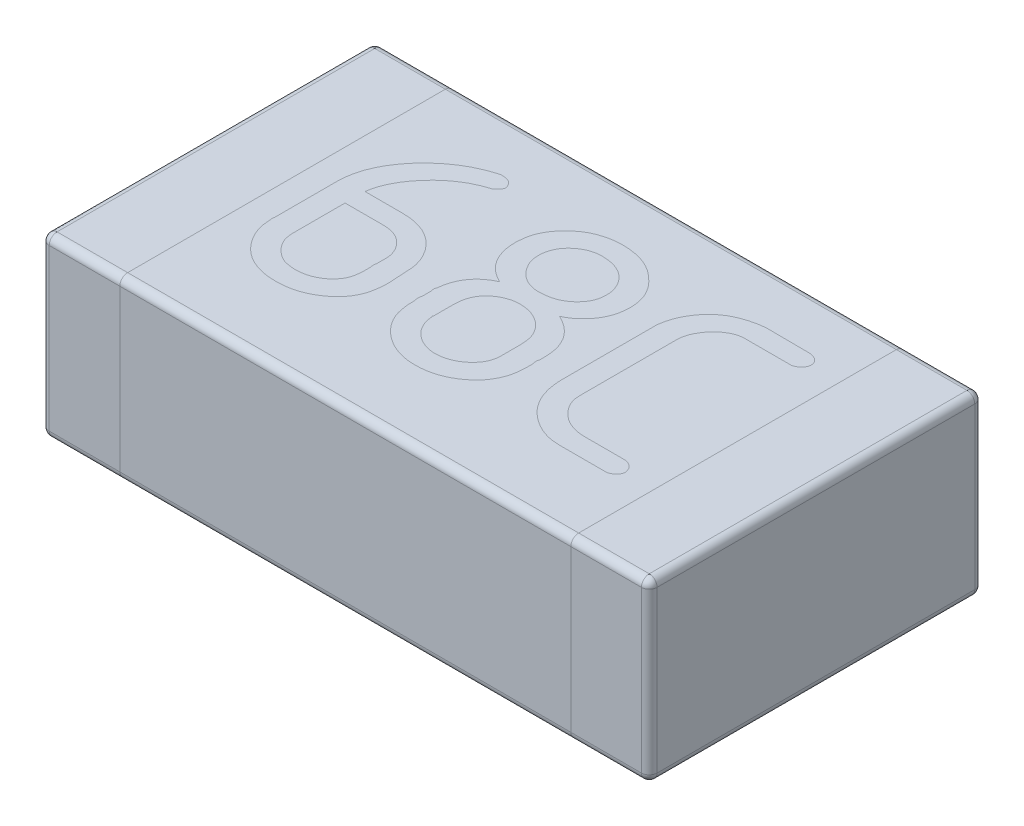
SolidWorks part; units mm, degrees
ref_plane "Front Plane" through (0, 0, 0) normal (0, 0, 1) x (1, 0, 0)
ref_plane "Top Plane" through (0, 0, 0) normal (0, 1, 0) x (1, 0, 0)
ref_plane "Right Plane" through (0, 0, 0) normal (1, 0, 0) x (0, 0, -1)
sketch "Sketch1" plane through (0, 0, 0) normal (0, 1, 0) x (1, 0, 0)
  line L1 (-0.755, -0.425) -> (0.755, -0.425)
  line L2 (-0.775, -0.405) -> (-0.775, 0.405)
  line L3 (-0.755, 0.425) -> (0.755, 0.425)
  line L4 (0.775, -0.405) -> (0.775, 0.405)
  line L5 (-0.775, -0.425) -> (0.775, 0.425) construction
  line L6 (-0.775, 0.425) -> (0.775, -0.425) construction
  arc A4 (-0.775, -0.405) -> (-0.755, -0.425) centre (-0.755, -0.405) ccw
  arc A5 (0.755, -0.425) -> (0.775, -0.405) centre (0.755, -0.405) ccw
  arc A6 (0.775, 0.405) -> (0.755, 0.425) centre (0.755, 0.405) ccw
  arc A7 (-0.755, 0.425) -> (-0.775, 0.405) centre (-0.755, 0.405) ccw
  point P0 (0, 0)
  dimension "D4" = 0.02
  dimension "D1" = 1.55
  dimension "D2" = 0.85
extrude "Boss-Extrude1" add sketch "Sketch1" along normal mid plane 0.45
sketch "Sketch3" plane through (0, 0.225, 0) normal (0, 1, 0) x (1, 0, 0)
  line L0 (-0.575, 0) -> (0.575, 0) construction
  line L1 (-0.575, -0.5133) -> (-0.575, 0.5133)
  line L2 (0.575, -0.5133) -> (0.575, 0.5133)
  line L3 (0, -0.25) -> (0, 0.25) construction
  line L6 (-0.575, -0.25) -> (0.575, -0.25) construction
  text T0 "<b>68C</b>" font "SWIsop1" height 0.53
  point P4 (0, 0)
  point P8 (-0.575, 0)
  point P11 (0.575, 0)
  point P14 (0, 0)
  point P17 (0, -0.25)
  dimension "D1" = 1.15
  dimension "D2" = 0.5
sketch "Sketch4" plane through (0, 0, 0.425) normal (0, 0, 1) x (1, 0, 0)
  line L0 (-0.575, 0.225) -> (-0.575, -0.5946)
  line L1 (0.575, 0.225) -> (0.575, -0.5946)
sketch "Sketch5" plane through (0, 0, -0.425) normal (0, 0, -1) x (-1, 0, 0)
  line L0 (-0.575, 0.225) -> (-0.575, -0.5946) construction
  line L1 (-0.575, 0.225) -> (-0.575, -0.5946)
  line L2 (0.575, 0.225) -> (0.575, -0.5946) construction
  line L3 (0.575, 0.225) -> (0.575, -0.5946)
sketch "Sketch6" plane through (0, -0.225, 0) normal (0, -1, 0) x (1, 0, 0)
  line L0 (0.575, 0.5133) -> (0.575, -0.5133) construction
  line L1 (-0.575, 0.5133) -> (-0.575, -0.5133) construction
  line L2 (0.575, 0.5133) -> (0.575, -0.5133)
  line L3 (-0.575, 0.5133) -> (-0.575, -0.5133)
split line "Split Line2"
split line "Split Line3"
split line "Split Line4"
split line "Split Line5"
fillet "Fillet2" radius 0.02 24 edges at (0.7691, 0.225, 0.4191) (-0.665, -0.225, 0.425) (-0.7691, -0.225, 0.4191) (0, 0.225, 0.425) (-0.665, 0.225, -0.425) (0, 0.225, -0.425) (0.665, 0.225, 0.425) (0.775, 0.225, 0) (0, -0.225, 0.425) (0.665, -0.225, 0.425) (0, -0.225, -0.425) (-0.665, -0.225, -0.425) (0.7691, 0.225, -0.4191) (0.665, 0.225, -0.425) (-0.7691, 0.225, -0.4191) (-0.775, 0.225, 0) (-0.7691, 0.225, 0.4191) (-0.665, 0.225, 0.425) (-0.775, -0.225, 0) (-0.7691, -0.225, -0.4191) (0.665, -0.225, -0.425) (0.7691, -0.225, -0.4191) (0.775, -0.225, 0) (0.7691, -0.225, 0.4191)
